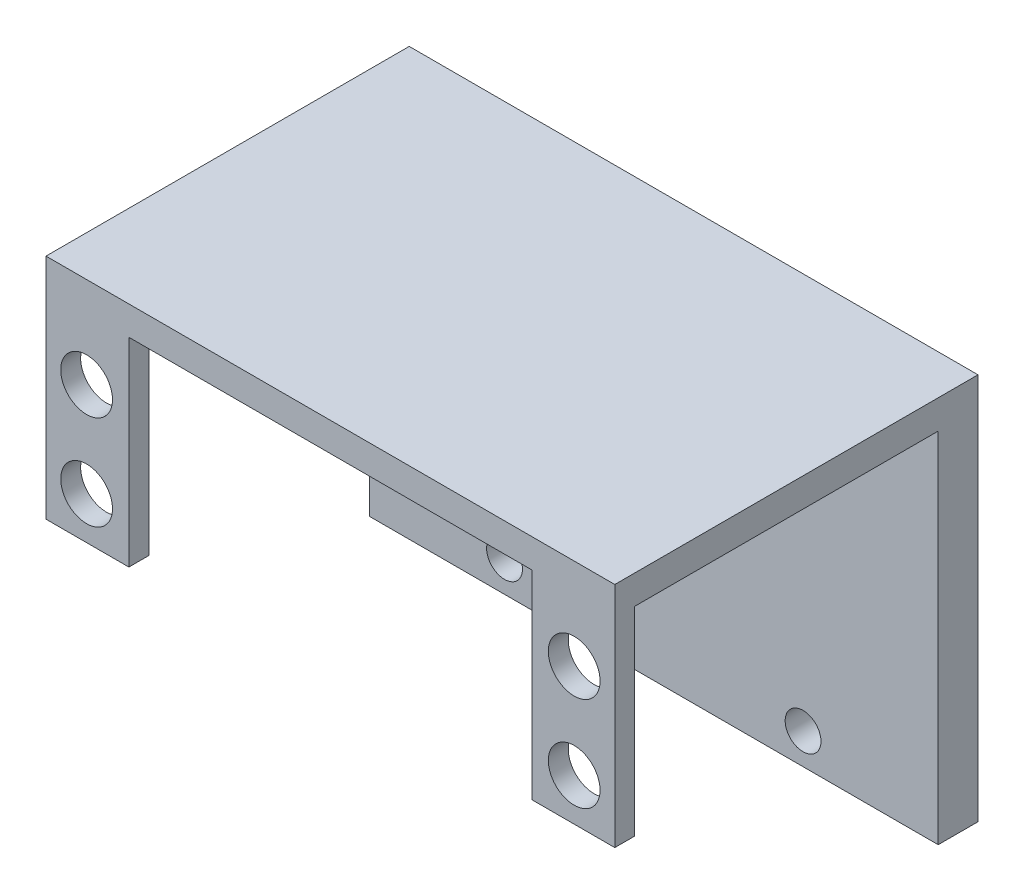
SolidWorks part; units mm, degrees
ref_plane "前视基准面" through (0, 0, 0) normal (0, 0, 1) x (1, 0, 0)
ref_plane "上视基准面" through (0, 0, 0) normal (0, 1, 0) x (1, 0, 0)
ref_plane "右视基准面" through (0, 0, 0) normal (1, 0, 0) x (0, 0, -1)
sketch "草图1" plane through (0, 0, 0) normal (0, 0, 1) x (1, 0, 0)
  line L1 (-20.25, 10) -> (-20.25, -10) construction
  line L2 (0, -10) -> (0, 0) construction
  line L3 (-10.1089, -10) -> (20.25, -10) construction
  line L4 (-20.25, -9) -> (-28.5798, -9)
  line L9 (20.25, -9) -> (28.5798, -9)
  line L10 (-20.25, -9) -> (-20.25, 9)
  line L11 (20.25, -9) -> (20.25, 9)
  line L13 (-28.5798, 12) -> (28.5798, 12)
  line L15 (-20.25, 9) -> (-20.25, 10)
  line L16 (-20.25, 10) -> (20.25, 10)
  line L17 (20.25, 10) -> (20.25, 9)
  line L18 (-28.5798, -9) -> (-28.5798, 12)
  line L19 (28.5798, -9) -> (28.5798, 12)
  circle A0 centre (-24.5, -4.75) radius 2.6
  circle A1 centre (-24.5, 4.75) radius 2.6
  circle A2 centre (24.5, 4.75) radius 2.6
  circle A3 centre (24.5, -4.75) radius 2.6
  point P6 (-20.25, 6.987)
  point P18 (20.25, 6.987)
  dimension "D1" = 5.2
  dimension "D2" = 5.2
  dimension "D3" = 2
extrude "凸台-拉伸3" add sketch "草图1" along normal blind 2
sketch "草图3" plane through (0, 0, 0) normal (0, 0, -1) x (-1, 0, 0)
  line L0 (28.5798, -9) -> (28.5798, 12) construction
  line L2 (-28.5798, 12) -> (-28.5798, 10)
  line L3 (-28.5798, 10) -> (28.5798, 10)
  line L4 (28.5798, 12) -> (28.5798, 10)
  line L5 (-28.5798, 12) -> (-28.5798, 21.9)
  line L6 (-28.5798, 21.9) -> (28.5798, 21.9)
  line L7 (28.5798, 21.9) -> (28.5798, 12)
extrude "凸台-拉伸5" add sketch "草图3" along normal blind 18.7 and the other way up to surface (2 mm away) other way up to face at (27.1, 4.75, 2)
sketch "草图9" plane through (0, 0, 2) normal (0, 0, 1) x (1, 0, 0)
  line L1 (-28.5798, 21.9) -> (28.5798, 21.9)
  line L2 (-28.5798, 21.9) -> (-28.5798, 10)
  line L3 (-28.5798, 10) -> (28.5798, 10)
  line L4 (28.5798, 21.9) -> (28.5798, 10)
extrude "凸台-拉伸6" add sketch "草图9" against normal blind 31.5
sketch "草图10" plane through (0, 0, -29.5) normal (0, 0, -1) x (-1, 0, 0)
  line L4 (28.5798, 10) -> (28.5798, 21.9)
  line L5 (28.5798, 21.9) -> (-28.5798, 21.9)
  line L6 (-28.5798, 21.9) -> (-28.5798, 10)
  line L7 (-28.5798, 10) -> (28.5798, 10)
  line L8 (28.5798, 10) -> (28.5798, 21.9)
  line L9 (28.5798, 21.9) -> (-28.5798, 21.9)
  line L10 (-28.5798, 21.9) -> (-28.5798, 10)
  line L11 (-28.5798, 10) -> (28.5798, 10)
  dimension "D1" = 0
extrude "凸台-拉伸7" add sketch "草图10" along normal blind 5
sketch "草图11" plane through (0, 21.9, 0) normal (0, 1, 0) x (1, 0, 0)
  line L4 (-28.5798, 34.5) -> (-28.5798, -2)
  line L5 (-28.5798, -2) -> (28.5798, -2)
  line L6 (28.5798, -2) -> (28.5798, 34.5)
  line L7 (28.5798, 34.5) -> (-28.5798, 34.5)
  line L8 (-28.5798, 34.5) -> (-28.5798, -2)
  line L9 (-28.5798, -2) -> (28.5798, -2)
  line L10 (28.5798, -2) -> (28.5798, 34.5)
  line L11 (28.5798, 34.5) -> (-28.5798, 34.5)
  dimension "D1" = 0
extrude "切除-拉伸1" cut sketch "草图11" against normal blind 10
sketch "草图12" plane through (0, 10, 0) normal (0, -1, 0) x (1, 0, 0)
  line L0 (-28.5798, 0) -> (-28.5798, -34.5) construction
  line L1 (28.5798, -34.5) -> (-28.5798, -34.5)
  line L2 (28.5798, -34.5) -> (28.5798, -30.5)
  line L3 (28.5798, -30.5) -> (-28.5798, -30.5)
  line L4 (-28.5798, -34.5) -> (-28.5798, -30.5)
  dimension "D1" = 4
extrude "凸台-拉伸8" add sketch "草图12" along normal blind 35
sketch "草图13" plane through (0, 0, -34.5) normal (0, 0, -1) x (-1, 0, 0)
  line L0 (17.5, -21.8977) -> (17.5, 8.1023) construction
  line L1 (15, 10.6023) -> (-15, 10.6023) construction
  line L2 (-17.5, 8.1023) -> (-17.5, -21.8977) construction
  line L3 (-15, -24.3977) -> (15, -24.3977) construction
  line L4 (-28.5798, 11.9) -> (28.5798, 11.9) construction
  circle A0 centre (-15, 8.1023) radius 1.8
  circle A1 centre (15, -21.8977) radius 1.8
  arc A2 (15, -24.3977) -> (17.5, -21.8977) centre (15, -21.8977) ccw construction
  arc A3 (17.5, 8.1023) -> (15, 10.6023) centre (15, 8.1023) ccw construction
  arc A4 (-15, 10.6023) -> (-17.5, 8.1023) centre (-15, 8.1023) ccw construction
  arc A5 (-17.5, -21.8977) -> (-15, -24.3977) centre (-15, -21.8977) ccw construction
  circle A6 centre (-15, -21.8977) radius 1.8
  circle A7 centre (15, 8.1023) radius 1.8
  dimension "D1" = 30
  dimension "D2" = 35
  dimension "D3" = 17.5
  dimension "D4" = 3.7977
extrude "切除-拉伸2" cut sketch "草图13" against normal blind 10
sketch "草图14" plane through (0, 11.9, 0) normal (0, 1, 0) x (1, 0, 0)
  line L4 (28.5798, 34.5) -> (-28.5798, 34.5)
  line L5 (-28.5798, 34.5) -> (-28.5798, -2)
  line L6 (-28.5798, -2) -> (28.5798, -2)
  line L7 (28.5798, -2) -> (28.5798, 34.5)
  line L8 (28.5798, 34.5) -> (-28.5798, 34.5)
  line L9 (-28.5798, 34.5) -> (-28.5798, -2)
  line L10 (-28.5798, -2) -> (28.5798, -2)
  line L11 (28.5798, -2) -> (28.5798, 34.5)
  dimension "D1" = 0
extrude "凸台-拉伸9" add sketch "草图14" along normal blind 2
sketch "草图15" plane through (0, 10, 0) normal (0, -1, 0) x (1, 0, 0)
  line L8 (-28.5798, -30.5) -> (28.5798, -30.5)
  line L9 (28.5798, -30.5) -> (28.5798, 0)
  line L10 (28.5798, 0) -> (20.25, 0)
  line L11 (20.25, 0) -> (20.25, 2)
  line L12 (20.25, 2) -> (-20.25, 2)
  line L13 (-20.25, 2) -> (-20.25, 0)
  line L14 (-20.25, 0) -> (-28.5798, 0)
  line L15 (-28.5798, 0) -> (-28.5798, -30.5)
  line L16 (-28.5798, -30.5) -> (28.5798, -30.5)
  line L17 (28.5798, -30.5) -> (28.5798, 0)
  line L18 (28.5798, 0) -> (20.25, 0)
  line L19 (20.25, 0) -> (20.25, 2)
  line L20 (20.25, 2) -> (-20.25, 2)
  line L21 (-20.25, 2) -> (-20.25, 0)
  line L22 (-20.25, 0) -> (-28.5798, 0)
  line L23 (-28.5798, 0) -> (-28.5798, -30.5)
  dimension "D1" = 0
extrude "切除-拉伸3" cut sketch "草图15" against normal blind 1
